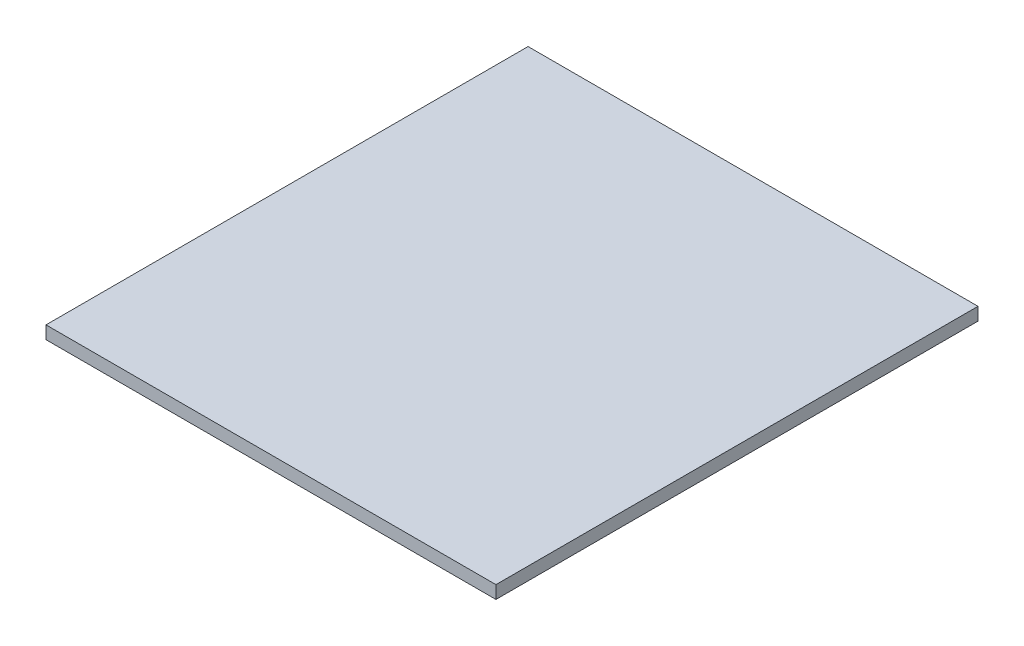
SolidWorks part; units mm, degrees
ref_plane "Front Plane" through (0, 0, 0) normal (0, 0, 1) x (1, 0, 0)
ref_plane "Top Plane" through (0, 0, 0) normal (0, 1, 0) x (1, 0, 0)
ref_plane "Right Plane" through (0, 0, 0) normal (1, 0, 0) x (0, 0, -1)
sketch "Sketch1" plane through (0, 0, 0) normal (0, 1, 0) x (1, 0, 0)
  line L1 (-70, -75) -> (70, -75)
  line L2 (-70, -75) -> (-70, 75)
  line L3 (-70, 75) -> (70, 75)
  line L4 (70, -75) -> (70, 75)
  line L5 (-70, -75) -> (70, 75) construction
  line L6 (-70, 75) -> (70, -75) construction
  point P0 (0, 0)
  dimension "D1" = 150
  dimension "D2" = 140
extrude "body" add sketch "Sketch1" along normal blind 4
